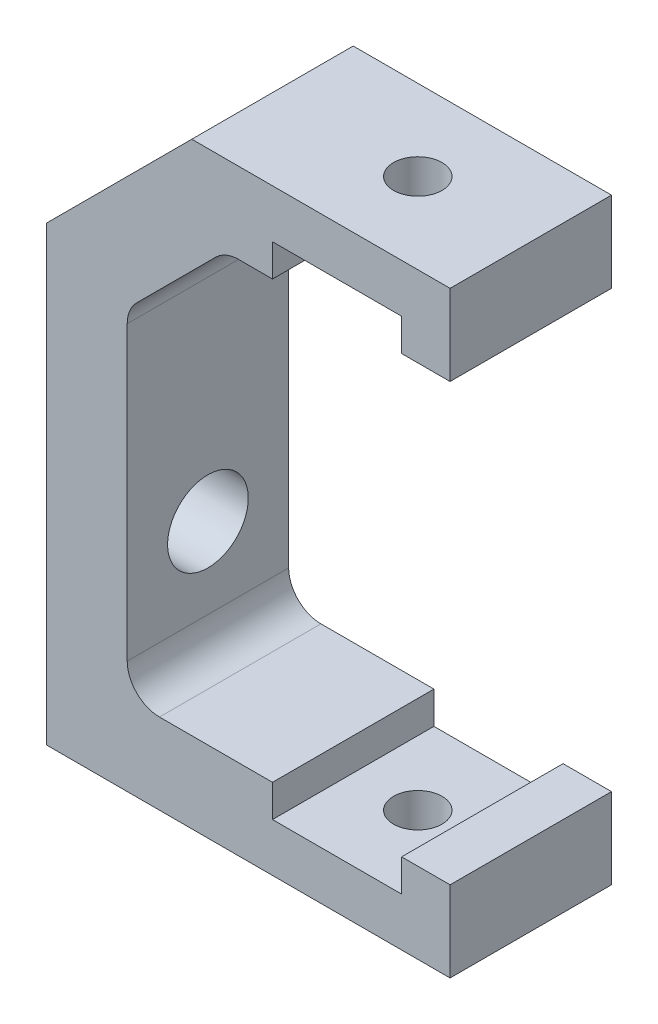
SolidWorks part; units mm, degrees
ref_plane "Front Plane" through (0, 0, 0) normal (0, 0, 1) x (1, 0, 0)
ref_plane "Top Plane" through (0, 0, 0) normal (0, 1, 0) x (1, 0, 0)
ref_plane "Right Plane" through (0, 0, 0) normal (1, 0, 0) x (0, 0, -1)
sketch "Sketch1" plane through (0, 0, 0) normal (0, 0, 1) x (1, 0, 0)
  line L0 (0, 0) -> (25, 0)
  line L1 (25, 0) -> (25, 5)
  line L2 (25, 5) -> (22, 5)
  line L3 (22, 5) -> (22, 3)
  line L4 (22, 3) -> (14, 3)
  line L5 (14, 3) -> (14, 5)
  line L6 (14, 5) -> (7, 5)
  line L7 (0, 0) -> (0, 28)
  line L9 (9, 37) -> (25, 37)
  line L10 (25, 37) -> (25, 32)
  line L11 (25, 32) -> (22, 32)
  line L12 (22, 32) -> (22, 34)
  line L13 (22, 34) -> (14, 34)
  line L14 (14, 34) -> (14, 32)
  line L17 (5, 25.1005) -> (5, 7)
  line L18 (0, 28) -> (9, 37)
  line L19 (14, 32) -> (11.8995, 32)
  line L20 (10.4853, 31.4142) -> (5.5858, 26.5147)
  arc A3 (7, 5) -> (5, 7) centre (7, 7) cw
  arc A6 (10.4853, 31.4142) -> (11.8995, 32) centre (11.8995, 30) cw
  arc A7 (5.5858, 26.5147) -> (5, 25.1005) centre (7, 25.1005) ccw
  point P4 (0, 37)
  point P24 (0, 0)
  point P25 (12.6001, 31.6544)
  point P26 (10.495, 31.4142)
  dimension "D1" = 2
  dimension "D4" = 8
  dimension "D13" = 2
  dimension "D2" = 5
  dimension "D3" = 25
  dimension "D5" = 9
  dimension "D6" = 45
  dimension "D7" = 37
  dimension "D8" = 5
  dimension "D9" = 5
  dimension "D10" = 2
  dimension "D11" = 2
  dimension "D12" = 3
  dimension "D14" = 5
extrude "Boss-Extrude1" add sketch "Sketch1" along normal blind 10
sketch "Sketch2" plane through (0, 37, 0) normal (0, 1, 0) x (1, 0, 0)
  line L3 (25, -10) -> (25, 0) construction
  circle A0 centre (18, -5) radius 1.5
  point P2 (0, 0)
  point P11 (25, -5)
  dimension "D1" = 3
  dimension "D2" = 7
extrude "Cut-Extrude1" cut sketch "Sketch2" against normal blind 38
sketch "Sketch3" plane through (0, 0, 0) normal (-1, 0, 0) x (0, 0, 1)
  line L1 (10, 0) -> (0, 0) construction
  line L2 (0, 28) -> (0, 0) construction
  circle A0 centre (5, 12) radius 2.5
  point P4 (0, 0)
  dimension "D1" = 5
  dimension "D2" = 12
  dimension "D3" = 5
extrude "Cut-Extrude2" cut sketch "Sketch3" against normal up to next
